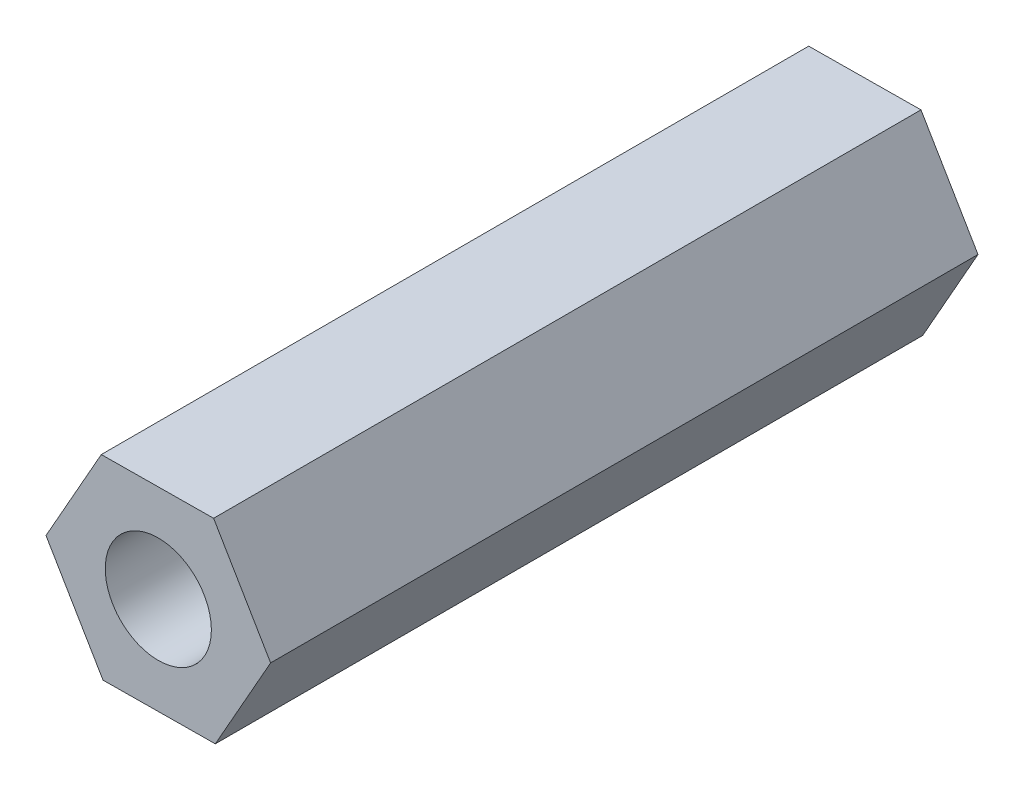
SolidWorks part; units mm, degrees
ref_plane "前视基准面" through (0, 0, 0) normal (0, 0, 1) x (1, 0, 0)
ref_plane "上视基准面" through (0, 0, 0) normal (0, 1, 0) x (1, 0, 0)
ref_plane "右视基准面" through (0, 0, 0) normal (1, 0, 0) x (0, 0, -1)
sketch "草图1" plane through (0, 0, 0) normal (0, 0, 1) x (1, 0, 0)
  line L1 (1.6119, -2.7359) -> (3.1753, 0.028)
  line L2 (3.1753, 0.028) -> (1.5634, 2.7639)
  line L3 (1.5634, 2.7639) -> (-1.6119, 2.7359)
  line L4 (-1.6119, 2.7359) -> (-3.1753, -0.028)
  line L5 (-3.1753, -0.028) -> (-1.5634, -2.7639)
  line L6 (-1.5634, -2.7639) -> (1.6119, -2.7359)
  circle A0 centre (0, 0) radius 2.75 construction
  circle A1 centre (0, 0) radius 1.5
extrude "凸台-拉伸1" add sketch "草图1" along normal blind 20
